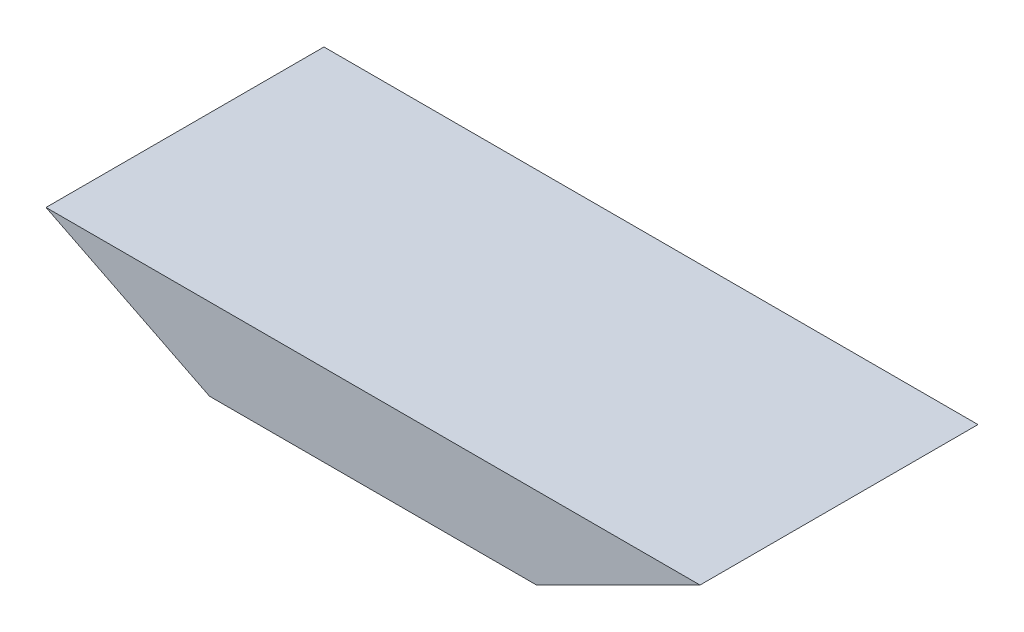
SolidWorks part; units mm, degrees
ref_plane "Front Plane" through (0, 0, 0) normal (0, 0, 1) x (1, 0, 0)
ref_plane "Top Plane" through (0, 0, 0) normal (0, 1, 0) x (1, 0, 0)
ref_plane "Right Plane" through (0, 0, 0) normal (1, 0, 0) x (0, 0, -1)
sketch "Croquis1" plane through (0, 0, 0) normal (0, 1, 0) x (1, 0, 0)
  line L0 (0, 8.5) -> (5, 0) construction
  line L1 (-20, -8.5) -> (20, -8.5)
  line L2 (-20, -8.5) -> (-20, 8.5)
  line L3 (-20, 8.5) -> (20, 8.5)
  line L4 (20, -8.5) -> (20, 8.5)
  line L5 (-20, -8.5) -> (20, 8.5) construction
  line L6 (-20, 8.5) -> (20, -8.5) construction
  line L7 (5, 0) -> (5, -7.5) construction
  point P0 (0, 0)
  dimension "D1" = 17
  dimension "D2" = 40
  dimension "D8" = 8.5
extrude "Saliente-Extruir1" add sketch "Croquis1" along normal blind 5
sketch "Croquis2" plane through (0, 0, 8.5) normal (0, 0, 1) x (1, 0, 0)
  line L10 (-20, 5) -> (-20, 0)
  line L12 (-20, 5) -> (20, 5) construction
  line L13 (-5, 5) -> (-20, 5)
  line L14 (-5, 5) -> (-10, 0)
  line L15 (-20, 0) -> (20, 0) construction
  line L16 (-10, 0) -> (-20, 0)
  dimension "D1" = 15
  dimension "D2" = 10
extrude "Cortar-Extruir1" cut sketch "Croquis2" against normal blind 40
sketch "Croquis3" plane through (0, 0, -8.5) normal (0, 0, -1) x (-1, 0, 0)
  line L0 (5, 5) -> (10, 5)
  line L1 (10, 5) -> (10, 0)
  line L6 (10, 0) -> (5, 5)
  line L7 (5, 5) -> (-20, 5)
  line L8 (-20, 5) -> (-20, 0)
  line L9 (-20, 0) -> (10, 0)
  line L11 (5, 5) -> (-20, 5)
  line L12 (-20, 5) -> (-20, 0)
  line L13 (-20, 0) -> (10, 0)
  line M5 (10, 0) -> (5, 5)
  dimension "D1" = 0
extrude "Saliente-Extruir2" add sketch "Croquis3" against normal blind 17 contours L1 L0 M5
sketch "Croquis4" plane through (0, 0, -8.5) normal (0, 0, -1) x (-1, 0, 0)
  line L0 (10, 5) -> (0, 0)
  line L1 (0, 0) -> (10, 0)
  line L2 (10, 0) -> (10, 5)
extrude "Cortar-Extruir2" cut sketch "Croquis4" against normal blind 17
sketch "Croquis5" plane through (0, 0, -8.5) normal (0, 0, -1) x (-1, 0, 0)
  line L4 (-20, 5) -> (-30, 5)
  line L5 (-30, 5) -> (-20, 0)
  line L6 (-20, 5) -> (-20, 0)
  dimension "D1" = 10
extrude "Saliente-Extruir3" add sketch "Croquis5" against normal blind 17
